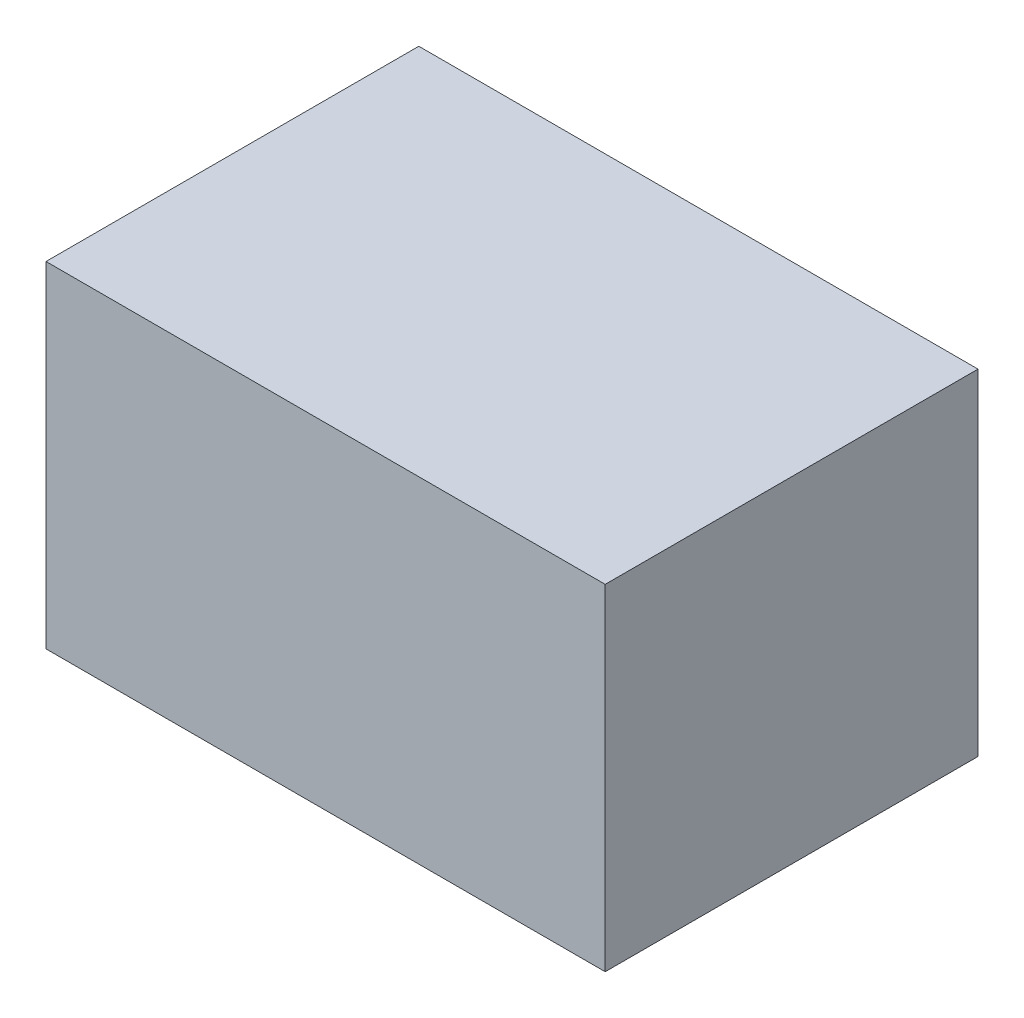
SolidWorks part; units mm, degrees
ref_plane "Front Plane" through (0, 0, 0) normal (0, 0, 1) x (1, 0, 0)
ref_plane "Top Plane" through (0, 0, 0) normal (0, 1, 0) x (1, 0, 0)
ref_plane "Right Plane" through (0, 0, 0) normal (1, 0, 0) x (0, 0, -1)
sketch "Sketch1" plane through (0, 0, 0) normal (0, 1, 0) x (1, 0, 0)
  line L1 (0, 0) -> (30, 0)
  line L2 (0, 0) -> (0, 20)
  line L3 (0, 20) -> (30, 20)
  line L4 (30, 0) -> (30, 20)
  dimension "D1" = 30
  dimension "D2" = 20
extrude "Boss-Extrude1" add sketch "Sketch1" along normal blind 18
